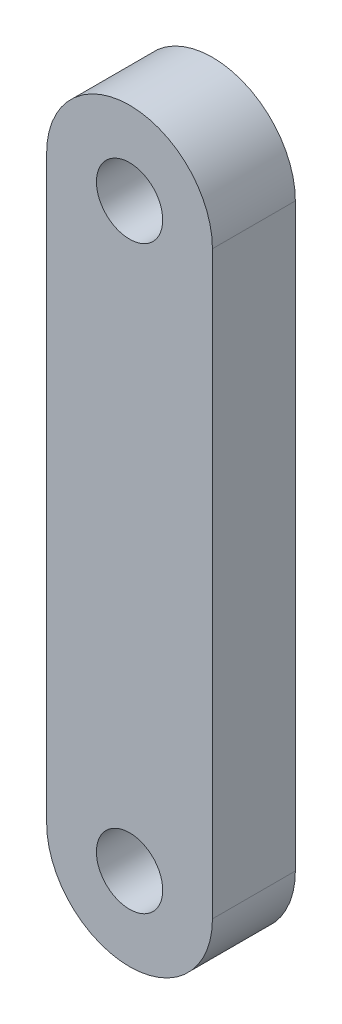
SolidWorks part; units mm, degrees
ref_plane "Front Plane" through (0, 0, 0) normal (0, 0, 1) x (1, 0, 0)
ref_plane "Top Plane" through (0, 0, 0) normal (0, 1, 0) x (1, 0, 0)
ref_plane "Right Plane" through (0, 0, 0) normal (1, 0, 0) x (0, 0, -1)
sketch "Sketch1" plane through (0, 0, 0) normal (0, 0, 1) x (1, 0, 0)
  line L0 (0, 17.5) -> (0, -17.5) construction
  line L1 (5, 17.5) -> (5, -17.5)
  line L2 (-5, 17.5) -> (-5, -17.5)
  arc A0 (5, 17.5) -> (-5, 17.5) centre (0, 17.5) ccw
  arc A1 (-5, -17.5) -> (5, -17.5) centre (0, -17.5) ccw
  point P3 (0, 0)
  point P8 (0, 0)
  dimension "D1" = 10
  dimension "D2" = 35
extrude "Boss-Extrude1" add sketch "Sketch1" along normal blind 5
hole_wizard "Ø4.0mm Dowel Hole1" positions "Sketch2" profile "Sketch3" hole size "Ø4.0" standard "ANSI Metric" end condition through all
sketch "Sketch2" plane through (0, 0, 5) normal (0, 0, 1) x (1, 0, 0)
  arc A0 (-5, -17.5) -> (5, -17.5) centre (0, -17.5) ccw construction
  arc A1 (5, 17.5) -> (-5, 17.5) centre (0, 17.5) ccw construction
  point P0 (0, 17.5)
  point P2 (0, -17.5)
  point P5 (0, 0)
  point P9 (0, 0)
sketch "Sketch3" plane through (0, 17.5, 5) normal (1, 0, 0) x (0, -1, 0)
  line L0 (0, 0) -> (0, 5)
  line L1 (0, 5) -> (2, 5)
  line L2 (2, 5) -> (2, 0)
  line L5 (2, 0) -> (0, 0)
  line L11 (0, -6.35) -> (0, 107.95) construction
  dimension "Thru Hole Dia." = 4
  dimension "Thru Hole Depth" = 5
